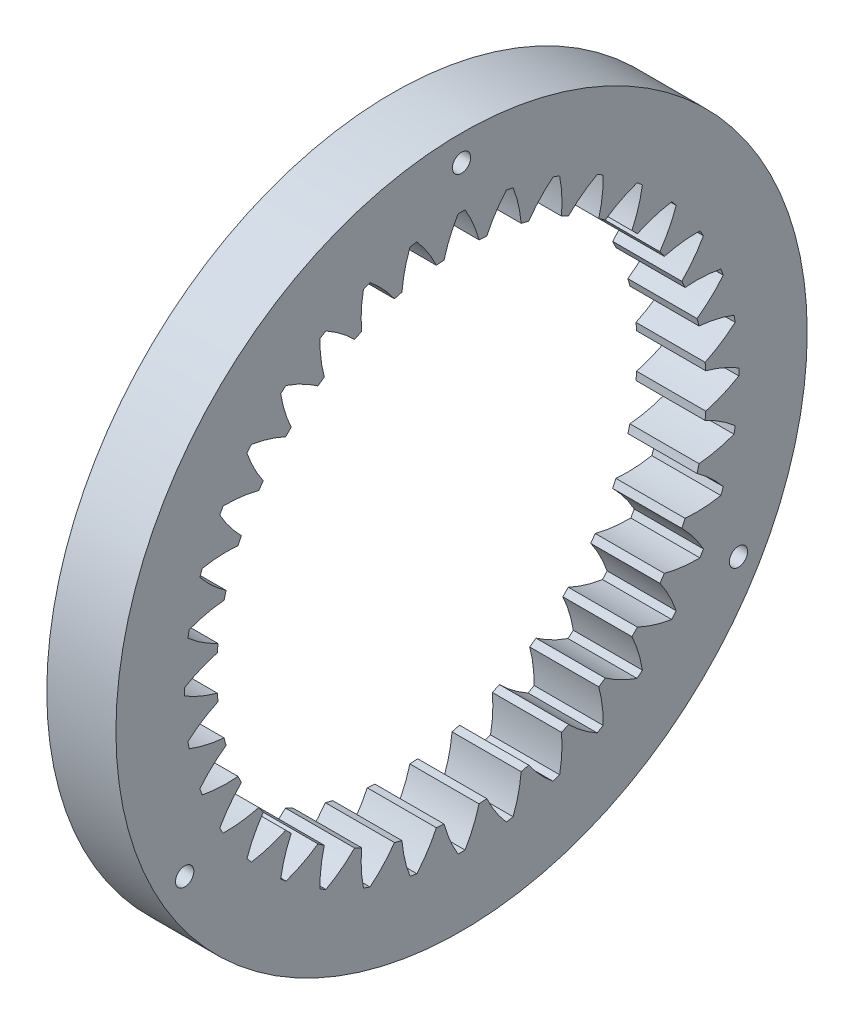
SolidWorks part; units mm, degrees
ref_plane "Plane1" through (0, 0, 0) normal (0, 0, 1) x (1, 0, 0)
ref_plane "Plane2" through (0, 0, 0) normal (0, 1, 0) x (1, 0, 0)
ref_plane "Plane3" through (0, 0, 0) normal (1, 0, 0) x (0, 0, -1)
other "Configuration Table"
sketch "HoldingSke" plane through (0, 0, 0) normal (0, 1, 0) x (1, 0, 0)
  line L0 (0, 0) -> (0.3236, -0.2351)
  line L1 (-15, 0) -> (100, 0) construction
  line L2 (0, 0) -> (-2.1039, 2.3779)
  line L3 (0, 0) -> (-11.863, 4.5341)
  line L4 (0, 0) -> (6.9867, 5.0761)
  line L5 (0, 0) -> (-23.7986, -8.8762)
  line L6 (0, 0) -> (-10.5278, -7.1032)
  line L7 (-2.1039, 2.3779) -> (3.3635, 27.1825)
  line L8 (-76.2, 4.8779) -> (-54.61, 4.8779)
  line L9 (-71.009, 38.7566) -> (-53.1078, 45.2721)
  line L10 (-76.2, 71.12) -> (104.1128, 71.12)
  line L11 (0, 0) -> (-12, 0)
  line L12 (-76.2, 101.6) -> (-76.113, 101.6)
  line L13 (24.9733, 27.94) -> (52.9518, 28.4284)
  line L14 (24.9733, 27.94) -> (24.9743, 27.94)
  line L15 (24.9733, 27.94) -> (100.4006, 29.5858)
  circle A0 centre (0, 0) radius 60
  circle A1 centre (0, 0) radius 12.7
  circle A2 centre (0, 0) radius 12.7
  dimension "MHD" = 25.4
  dimension "Hub_dia" = 25.4
  dimension "Diameter" = 120
  dimension "Num_teeth" = 36
  dimension "Pitch" = 0.4
  dimension "Overall_len" = 25.4
  dimension "Show_teeth" = 36
  dimension "Thickness" = 12.7
  dimension "OAL" = 25.4001
  dimension "T_dim" = 21.59
  dimension "Ap" = 20
  dimension "H" = 19.05
  dimension "Pitch_radius" = 180.3128
  dimension "Width" = 12
  dimension "Backlash" = 0.087
  dimension "Addendum_fac" = 1
  dimension "Dedendum_fac" = 1.25
  dimension "Clearance_fac" = 0.25
  dimension "Dedendum_add" = 0.001
  dimension "Module" = 2.5
sketch "BasProSke" plane through (0, 0, 0) normal (0, 1, 0) x (1, 0, 0)
  line L0 (-10, 0) -> (60, 0) construction
  line L1 (0, 42.5) -> (0, 60)
  line L2 (0, 42.5) -> (12, 42.5)
  line L3 (12, 42.5) -> (12, 60)
  line L4 (12, 60) -> (0, 60)
  dimension "Diameter" = 120
  dimension "Thickness" = 12
  dimension "Inside_diameter" = 85
revolve "Base-Revolve" add sketch "BasProSke" angle 360 about L0
sketch "TooCutSke" plane through (0, 0, 0) normal (1, 0, 0) x (0, 0, -1)
  line L3 (2.1804, 44.9471) -> (2.1804, 53.6633) construction
  line L4 (0, 0) -> (0, 59.563) construction
  line L5 (0, 0) -> (-5.9551, 68.0675) construction
  line L6 (-18.7007, 36.5668) -> (34.3819, 41.2109) construction
  circle A0 centre (0, 0) radius 45 construction
  circle A1 centre (0, 0) radius 48.126 construction
  circle A2 centre (0, 0) radius 38.0576 construction
  circle A3 centre (0, 0) radius 42.4746 construction
  arc A4 (3.0392, 42.3657) -> (0.6053, 48.1222) centre (-18.7007, 36.5668) ccw
  arc A5 (3.0392, 42.3657) -> (-3.0392, 42.3657) centre (0, 0) ccw
  arc A6 (0.6053, 48.1222) -> (-0.6053, 48.1222) centre (0, 0) ccw
  arc A7 (-0.6053, 48.1222) -> (-3.0392, 42.3657) centre (18.7007, 36.5668) ccw
  dimension "Pitch_dia" = 90
  dimension "Base_dia" = 76.1151
  dimension "Root_dia" = 96.252
  dimension "Overcut_dia" = 84.9492
  dimension "Flank_rad" = 22.5
  dimension "Half_ang" = 5
  dimension "Half_CT" = 2.1804
extrude "ToothCut" cut sketch "TooCutSke" along normal through all
fillet "Breaks" [suppressed] radius 0.25
fillet "RootFillets" [suppressed] radius 0.626
pattern_circular "TeethCuts" count 36 every 10 about axis through (-10, 0, 0) along (1, 0, 0) of "RootFillets", "Breaks", "ToothCut"
sketch "Croquis1" plane through (12, 0, 0) normal (1, 0, 0) x (0, 0, -1)
  line L0 (0, 0) -> (0, 55.5) construction
  circle A0 centre (0, 55.5) radius 1.5875
  circle A1 centre (48.0644, -27.75) radius 1.5875
  circle A2 centre (-48.0644, -27.75) radius 1.5875
  point P10 (0, 0)
  dimension "D1" = 3.175
  dimension "D2" = 55.5
  dimension "D3" = 3
extrude "Cortar-Extruir1" cut sketch "Croquis1" against normal through all
equation "' \"Module@HoldingSke\" = 6.35"
equation "' \"Num_teeth@HoldingSke\" = 24"
equation "' \"Ap@HoldingSke\" =  14.5"
equation "' \"Ap@HoldingSke\" = 14.5"
equation "' \"Width@HoldingSke\" = 12"
equation "' \"Diameter@HoldingSke\" = 8 * 25.4"
equation "' \"Show_teeth@HoldingSke\" = 100"
equation "' \"Backlash@HoldingSke\" = 0.009 * 25.4"
equation "' \"Addendum_fac@HoldingSke\" = 1.0"
equation "' \"Dedendum_fac@HoldingSke\" = 1.25"
equation "' \"Dedendum_add@HoldingSke\" = 0.00005 * 25.4"
equation "' \"Clearance_fac@HoldingSke\" = 0.25"
equation "\"Pitch@HoldingSke\" = 1 / \"Module@HoldingSke\" "
equation "\"Overcut_dia@TooCutSke\" = (\"Num_teeth@HoldingSke\" - 2 * \"Addendum_fac@HoldingSke\") / \"Pitch@HoldingSke\" - 0.002 * 25.4"
equation "\"Pitch_dia@TooCutSke\" = \"Num_teeth@HoldingSke\" / \"Pitch@HoldingSke\""
equation "\"Base_dia@TooCutSke\" = \"Num_teeth@HoldingSke\" / \"Pitch@HoldingSke\" * cos((\"Ap@HoldingSke\"  * 3.14159265 / 180)) * 0.90"
equation "\"Root_dia@TooCutSke\" = \"Num_teeth@HoldingSke\"  / \"Pitch@HoldingSke\" + 2 *  \"Dedendum_fac@HoldingSke\"/ \"Pitch@HoldingSke\" + \"Dedendum_add@HoldingSke\" * 2"
equation "\"Half_ang@TooCutSke\" = 180 / \"Num_teeth@HoldingSke\""
equation "\"Half_CT@TooCutSke\" = \"Num_teeth@HoldingSke\" / \"Pitch@HoldingSke\" * sin((3.14159265 / 2 / \"Num_teeth@HoldingSke\")) / 2 + 10 * \"Backlash@HoldingSke\" / 4"
equation "\"Flank_rad@TooCutSke\" = \"Num_teeth@HoldingSke\" / \"Pitch@HoldingSke\" / 4"
equation "\"Radius@RootFillets\"= \"Clearance_fac@HoldingSke\" / \"Pitch@HoldingSke\" + \"Dedendum_add@HoldingSke\""
equation "\"Break_rad@Breaks\" = 0.02 / \"Pitch@HoldingSke\" * 5"
equation "\"Num_teeth@TeethCuts\" = int( \"Show_teeth@HoldingSke\" ) + 1"
equation "\"Num_teeth@TeethCuts\" = ((sgn( \"Num_teeth@TeethCuts\" - \"Num_teeth@HoldingSke\" )-1)*( \"Num_teeth@TeethCuts\" - \"Num_teeth@HoldingSke\" ))/-2+ \"Num_teeth@HoldingSke\""
equation "\"Num_teeth@TeethCuts\" = ((sgn( \"Num_teeth@TeethCuts\" - 2.0)+1)*( \"Num_teeth@TeethCuts\" - 2.0))/2 +2.0"
equation "\"Angle@TeethCuts\" = 360.0 / \"Num_teeth@HoldingSke\""
equation "\"Diameter@BasProSke\" = \"Num_teeth@HoldingSke\"  / \"Pitch@HoldingSke\" + 2 *  \"Dedendum_fac@HoldingSke\"/ \"Pitch@HoldingSke\" + \"Dedendum_add@HoldingSke\" * 2 + 0.002 * 25.4"
equation "\"Diameter@BasProSke\" = ((sgn( \"Diameter@BasProSke\"  - \"Diameter@HoldingSke\" )+1)*( \"Diameter@BasProSke\"  - \"Diameter@HoldingSke\" ))/2 + \"Diameter@HoldingSke\""
equation "\"Inside_diameter@BasProSke\" =  (\"Num_teeth@HoldingSke\" - 2 * \"Addendum_fac@HoldingSke\") / \"Pitch@HoldingSke\" "
equation "\"Thickness@BasProSke\"  = \"Width@HoldingSke\""
